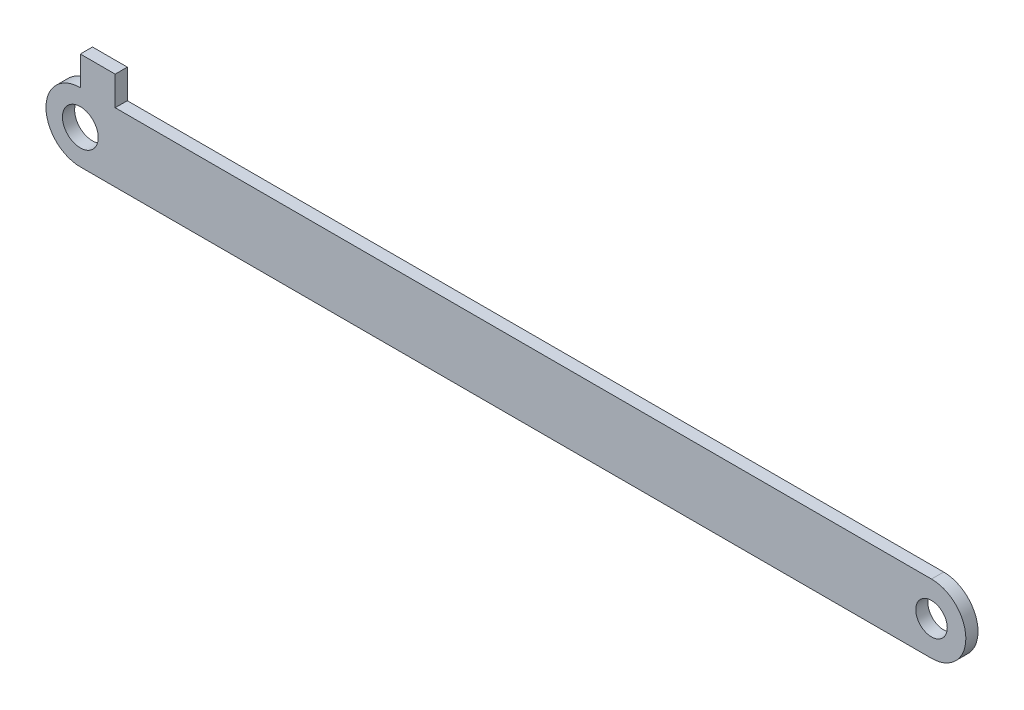
SolidWorks part; units mm, degrees
ref_plane "前视基准面" through (0, 0, 0) normal (0, 0, 1) x (1, 0, 0)
ref_plane "上视基准面" through (0, 0, 0) normal (0, 1, 0) x (1, 0, 0)
ref_plane "右视基准面" through (0, 0, 0) normal (1, 0, 0) x (0, 0, -1)
sketch "草图1" plane through (0, 0, 0) normal (0, 0, 1) x (1, 0, 0)
  line L0 (0, 0) -> (350, 0) construction
  line L1 (0, 14.1204) -> (350, 14.1204)
  line L2 (0, -14.1204) -> (350, -14.1204)
  arc A0 (0, 14.1204) -> (0, -14.1204) centre (0, 0) ccw
  arc A1 (350, -14.1204) -> (350, 14.1204) centre (350, 0) ccw
  circle A2 centre (0, 0) radius 7.353
  circle A3 centre (350, 0) radius 6.4856
  point P3 (175, 0)
  dimension "D1" = 350
extrude "凸台-拉伸1" add sketch "草图1" along normal blind 5
sketch "草图2" plane through (0, 0, 0) normal (0, 0, 1) x (1, 0, 0)
  line L0 (0, 14.1204) -> (0, 26.0938)
  line L1 (0, 26.0938) -> (14.324, 26.0938)
  line L2 (14.324, 26.0938) -> (14.324, 14.1204)
  line L3 (350, 14.1204) -> (0, 14.1204) construction
  line L6 (0, -14.1204) -> (350, -14.1204)
  line L7 (350, 14.1204) -> (0, 14.1204)
  line L9 (14.324, 14.1204) -> (0, 14.1204)
  arc A2 (0, 14.1204) -> (0, -14.1204) centre (0, 0) ccw
  arc A3 (350, -14.1204) -> (350, 14.1204) centre (350, 0) ccw
  dimension "D1" = 0
extrude "凸台-拉伸2" add sketch "草图2" along normal up to vertex (5 mm away)
